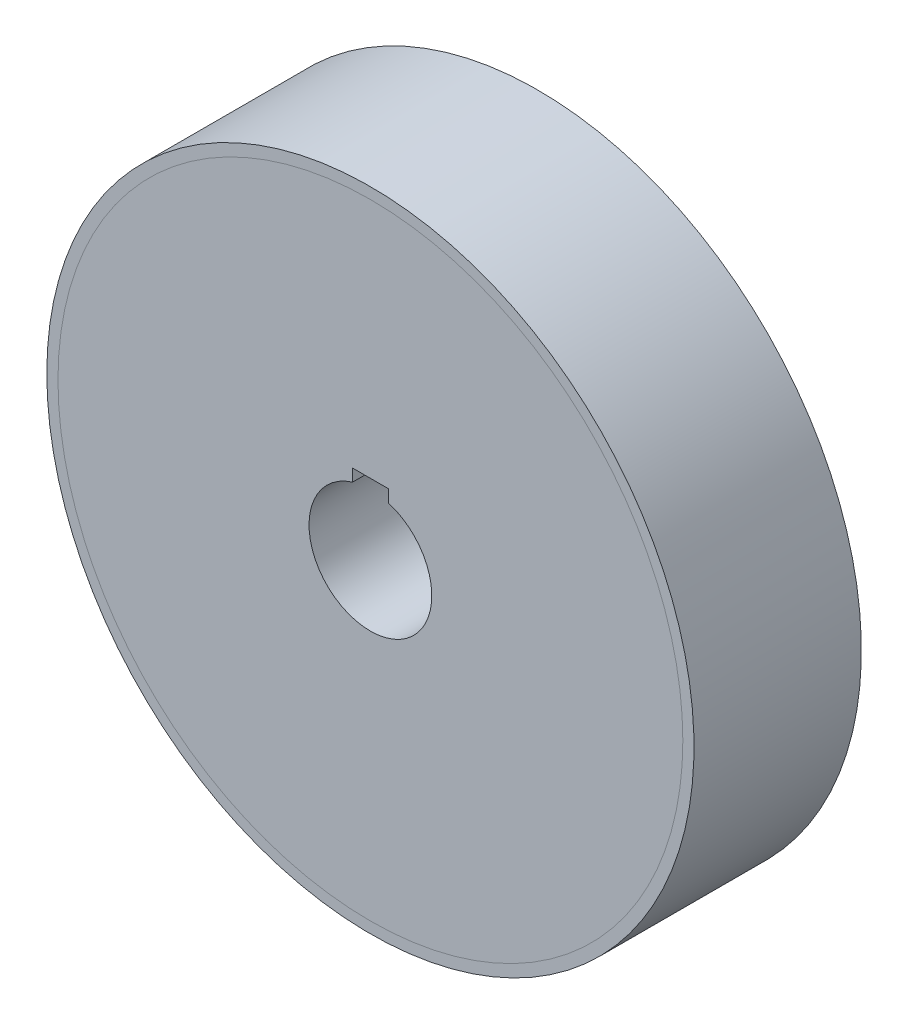
SolidWorks part; units mm, degrees
material "1.7225 (42CrMo4)"
ref_plane "Front Plane" through (0, 0, 0) normal (0, 0, 1) x (1, 0, 0)
ref_plane "Top Plane" through (0, 0, 0) normal (0, 1, 0) x (1, 0, 0)
ref_plane "Right Plane" through (0, 0, 0) normal (1, 0, 0) x (0, 0, -1)
sketch "Sketch1" plane through (0, 0, 0) normal (0, 0, 1) x (1, 0, 0)
  circle A0 centre (0, 0) radius 140
  dimension "D1" = 280
extrude "Boss-Extrude1" add sketch "Sketch1" along normal blind 75
sketch "Sketch2" plane through (0, 0, 0) normal (0, 0, -1) x (-1, 0, 0)
  circle A0 centre (0, 0) radius 27.5
  dimension "D1" = 55
extrude "Cut-Extrude1" cut sketch "Sketch2" against normal through all
sketch "Sketch3" plane through (0, 0, 0) normal (0, 0, -1) x (-1, 0, 0)
  line L0 (0, 0) -> (0, 140) construction
  line L1 (-8, 26.3106) -> (-8, 31.8)
  line L2 (-8, 31.8) -> (8, 31.8)
  line L3 (8, 26.3106) -> (8, 31.8)
  circle A0 centre (0, 0) radius 140 construction
  circle A1 centre (0, 0) radius 27.5 construction
  arc A2 (8, 26.3106) -> (-8, 26.3106) centre (0, 0) ccw
  point P13 (0, 31.8)
  dimension "D1" = 16
  dimension "D2" = 4.3
extrude "Cut-Extrude2" cut sketch "Sketch3" against normal through all
sketch "Sketch4" plane through (0, 0, 0) normal (0, 0, -1) x (-1, 0, 0)
  circle A0 centre (0, 0) radius 145
  circle A1 centre (0, 0) radius 140
  circle A2 centre (0, 0) radius 140
  dimension "D2" = 290
  dimension "D1" = 0
extrude "Boss-Extrude2" add sketch "Sketch4" against normal up to surface (75 mm away) separate body up to face at (0, 15.6027, 75)
